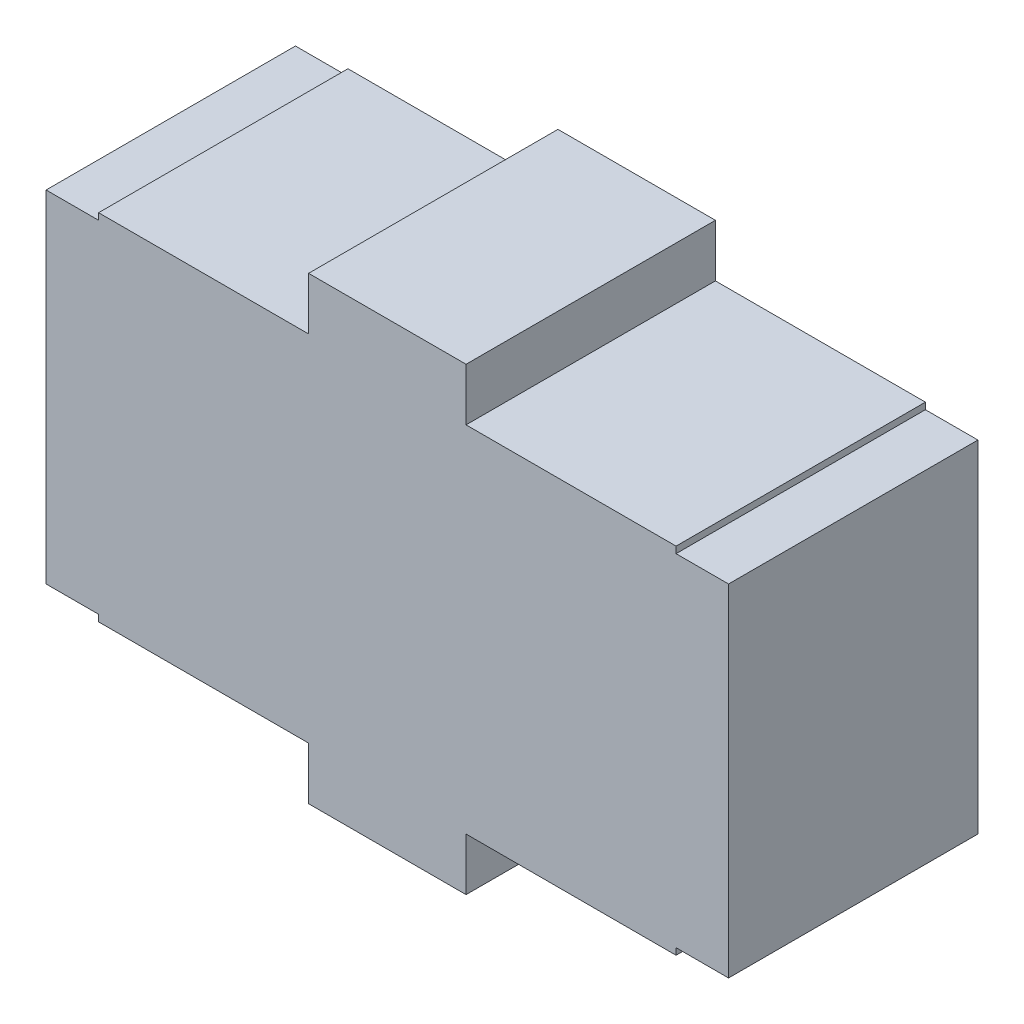
SolidWorks part; units mm, degrees
ref_plane "前视基准面" through (0, 0, 0) normal (0, 0, 1) x (1, 0, 0)
ref_plane "上视基准面" through (0, 0, 0) normal (0, 1, 0) x (1, 0, 0)
ref_plane "右视基准面" through (0, 0, 0) normal (1, 0, 0) x (0, 0, -1)
sketch "草图1" plane through (0, 0, 0) normal (0, 0, 1) x (1, 0, 0)
  line L0 (-0.3, -0.875) -> (-0.3, -0.675)
  line L1 (-0.3, -0.675) -> (-1.1, -0.675)
  line L2 (-1.1, -0.675) -> (-1.1, -0.65)
  line L3 (-1.1, -0.65) -> (-1.3, -0.65)
  line L4 (-1.3, -0.65) -> (-1.3, 0.65)
  line L5 (-1.3, 0.65) -> (-1.1, 0.65)
  line L6 (-1.1, 0.65) -> (-1.1, 0.675)
  line L7 (-1.1, 0.675) -> (-0.3, 0.675)
  line L8 (-0.3, 0.675) -> (-0.3, 0.875)
  line L9 (-0.3, 0.875) -> (0.3, 0.875)
  line L10 (0.3, 0.875) -> (0.3, 0.675)
  line L11 (0.3, 0.675) -> (1.1, 0.675)
  line L12 (1.1, 0.675) -> (1.1, 0.65)
  line L13 (1.1, 0.65) -> (1.3, 0.65)
  line L14 (1.3, 0.65) -> (1.3, -0.65)
  line L15 (1.3, -0.65) -> (1.1, -0.65)
  line L16 (1.1, -0.65) -> (1.1, -0.675)
  line L17 (1.1, -0.675) -> (0.3, -0.675)
  line L18 (0.3, -0.675) -> (0.3, -0.875)
  line L19 (0.3, -0.875) -> (-0.3, -0.875)
extrude "Component_Outline" add sketch "草图1" along normal blind 0.95 separate body
sketch3d "3D草图1"
  line L0 (0, 0, 0) -> (1, 0, 0)
  line L1 (0, 0, 0) -> (0, 1, 0)
  line L2 (0, 0, 0) -> (0, 0, 1)
  point P0 (0, 0, 0)
